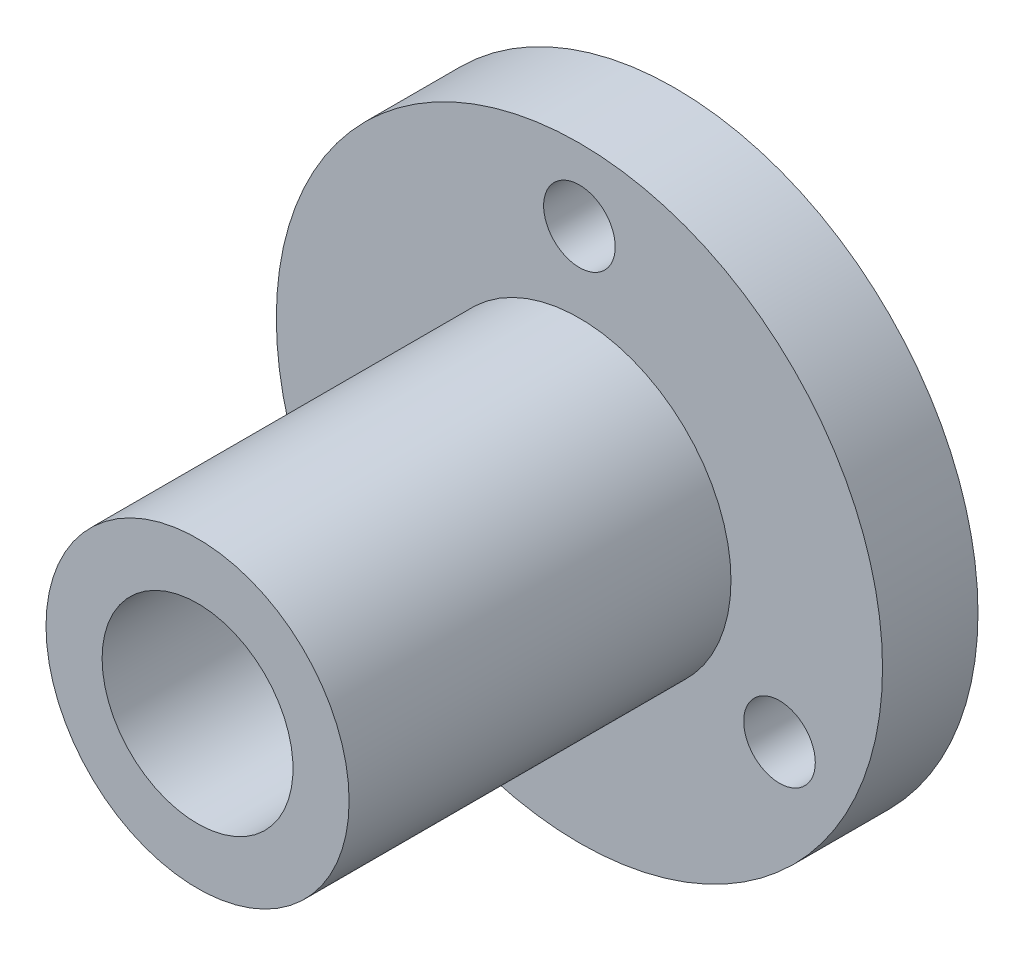
SolidWorks part; units mm, degrees
material "Nylon 101"
ref_plane "Front" through (0, 0, 0) normal (0, 0, 1) x (1, 0, 0)
ref_plane "Top" through (0, 0, 0) normal (0, 1, 0) x (1, 0, 0)
ref_plane "Right" through (0, 0, 0) normal (1, 0, 0) x (0, 0, -1)
sketch "Sketch1" plane through (0, 0, 0) normal (0, 0, 1) x (1, 0, 0)
  circle A0 centre (0, 0) radius 12.7
  dimension "D1" = 25.4
extrude "Boss-Extrude1" add sketch "Sketch1" along normal blind 4
sketch "Sketch2" plane through (0, 0, 4) normal (0, 0, 1) x (1, 0, 0)
  circle A0 centre (0, 0) radius 6.35
  dimension "D1" = 12.7
extrude "Boss-Extrude2" add sketch "Sketch2" along normal blind 16
sketch "Sketch3" plane through (0, 0, 0) normal (0, 0, -1) x (-1, 0, 0)
  circle A0 centre (0, 0) radius 4
  dimension "D1" = 8
extrude "Cut-Extrude1" cut sketch "Sketch3" against normal through all
sketch "Sketch4" plane through (0, 0, 4) normal (0, 0, 1) x (1, 0, 0)
  circle A0 centre (0, 0) radius 9.6796 construction
  circle A1 centre (0, 9.6796) radius 1.5
  circle A2 centre (0, 0) radius 9.6796 construction
  circle A3 centre (8.3828, -4.8398) radius 1.5
  circle A4 centre (0, 0) radius 9.6796 construction
  circle A5 centre (-8.3828, -4.8398) radius 1.5
  point P13 (0, 0)
  dimension "D1" = 19.3592
  dimension "D2" = 3
  dimension "D3" = 3
extrude "Cut-Extrude2" cut sketch "Sketch4" against normal through all
chamfer "Chamfer1" distance 1.5 angle 45 3 edges at (-6.8828, -4.8398, 0) (9.8828, -4.8398, 0) (1.5, 9.6796, 0)
